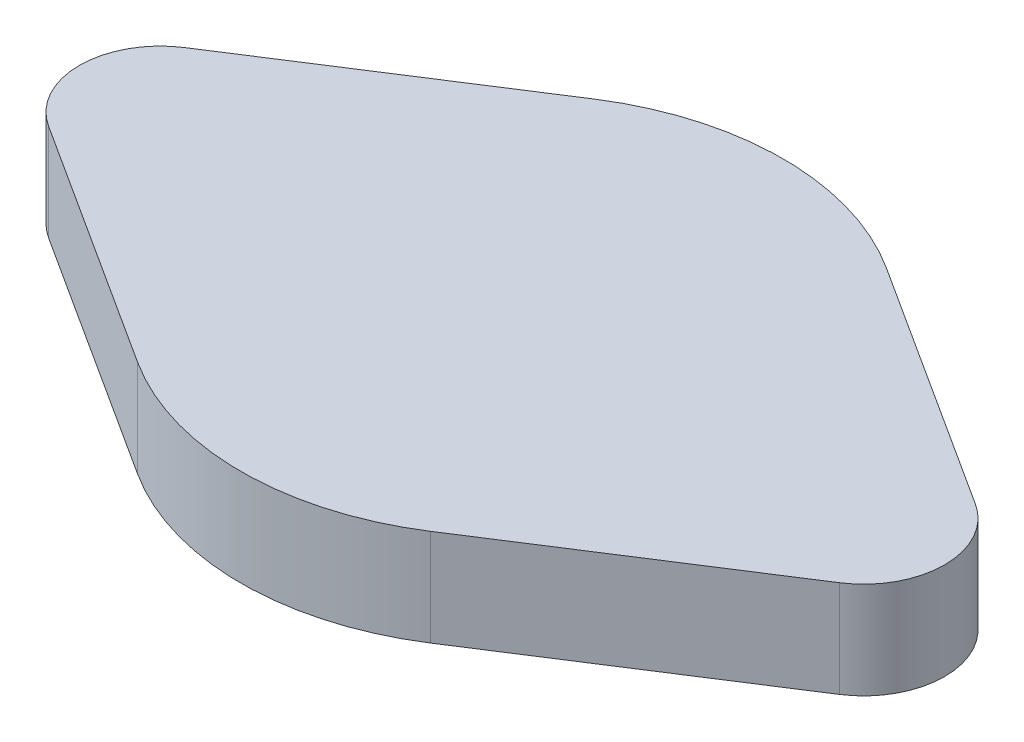
SolidWorks part; units mm, degrees
material "ABS"
ref_plane "Front Plane" through (0, 0, 0) normal (0, 0, 1) x (1, 0, 0)
ref_plane "Top Plane" through (0, 0, 0) normal (0, 1, 0) x (1, 0, 0)
ref_plane "Right Plane" through (0, 0, 0) normal (1, 0, 0) x (0, 0, -1)
sketch "Sketch1" plane through (0, 0, 0) normal (0, 1, 0) x (1, 0, 0)
  line L0 (18.1754, 0) -> (-18.1754, 0) construction
  line L1 (0, 0) -> (0, 8) construction
  line L2 (-20.4324, 3.5129) -> (-7.5676, 11.7784)
  line L3 (-21.3509, 0) -> (-19.7631, -2.75) construction
  line L4 (-19.7631, -2.75) -> (-16.5877, -2.75) construction
  line L5 (-16.5877, -2.75) -> (-15, 0) construction
  line L6 (-15, 0) -> (-16.5877, 2.75) construction
  line L7 (-16.5877, 2.75) -> (-19.7631, 2.75) construction
  line L8 (-19.7631, 2.75) -> (-21.3509, 0) construction
  line L9 (-20.4324, -3.5129) -> (-7.5676, -11.7784)
  line L10 (0, 0) -> (0, 17.7952) construction
  line L11 (20.4324, -3.5129) -> (7.5676, -11.7784)
  line L12 (20.4324, 3.5129) -> (7.5676, 11.7784)
  circle A0 centre (0, 0) radius 8 construction
  circle A1 centre (0, 0) radius 4.1 construction
  arc A6 (-7.5676, -11.7784) -> (7.5676, -11.7784) centre (0, 0) ccw
  circle A7 centre (-18.1754, 0) radius 1.6 construction
  circle A8 centre (18.1754, 0) radius 1.6 construction
  circle A9 centre (-18.1754, 0) radius 2.75 construction
  arc A10 (-20.4324, 3.5129) -> (-20.4324, -3.5129) centre (-18.1754, 0) ccw
  arc A11 (20.4324, 3.5129) -> (20.4324, -3.5129) centre (18.1754, 0) cw
  arc A12 (7.5676, 11.7784) -> (-7.5676, 11.7784) centre (0, 0) ccw
  circle A13 centre (8, 0) radius 1.6 construction
  circle A14 centre (0, 8) radius 1.6 construction
  circle A15 centre (-8, 0) radius 1.6 construction
  circle A16 centre (0, -8) radius 1.6 construction
  point P9 (0, 0)
  dimension "D1" = 16
  dimension "D2" = 8.2
  dimension "D4" = 3.2
  dimension "D6" = 28
  dimension "D7" = 3.2
  dimension "D9" = 15
  dimension "D3" = 90
  dimension "D8" = 5.5
extrude "Boss-Extrude1" add sketch "Sketch1" along normal blind 5
